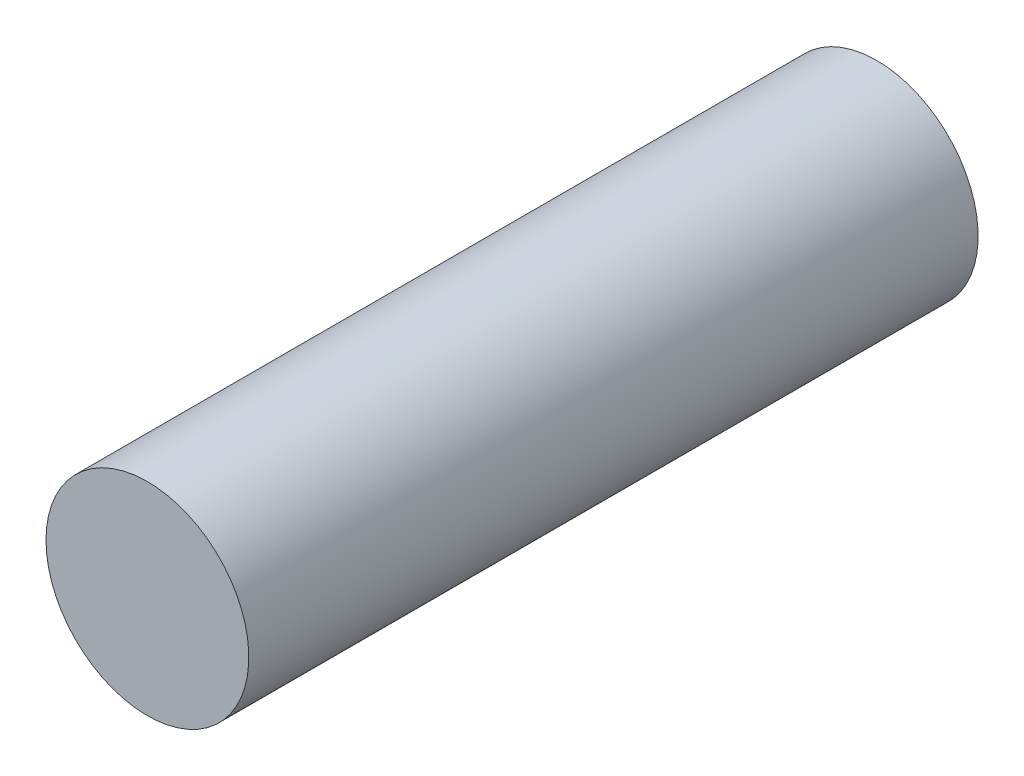
SolidWorks part; units mm, degrees
material "Custom Plastic"
ref_plane "X-Y Datum" through (0, 0, 0) normal (0, 0, 1) x (1, 0, 0)
ref_plane "X-Z Datum" through (0, 0, 0) normal (0, 1, 0) x (1, 0, 0)
ref_plane "Y-Z Datum" through (0, 0, 0) normal (1, 0, 0) x (0, 0, -1)
sketch "Sketch1" plane through (0, 0, 0) normal (0, 0, 1) x (1, 0, 0)
  circle A0 centre (0, 0) radius 3.302
  dimension "D1" = 6.604
extrude "Boss-Extrude1" add sketch "Sketch1" along normal mid plane 23.749
